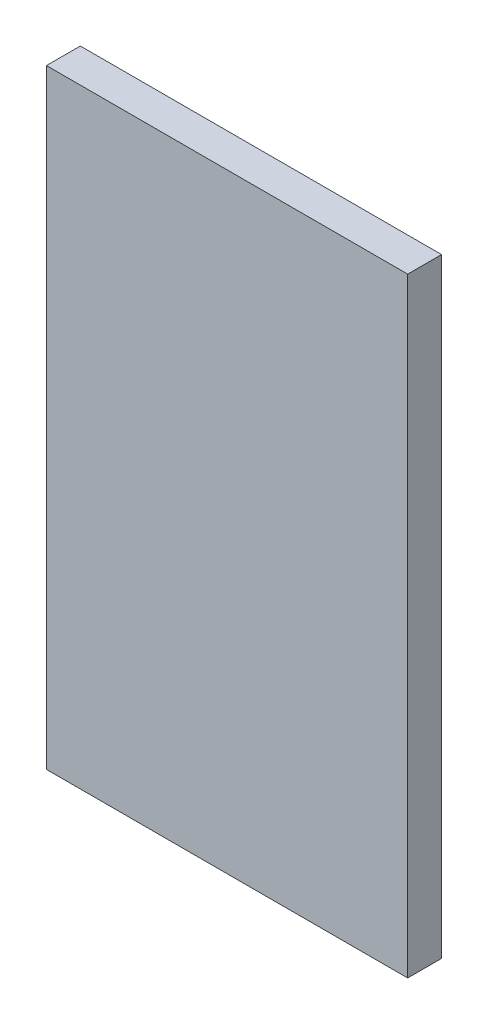
SolidWorks part; units mm, degrees
ref_plane "Front" through (0, 0, 0) normal (0, 0, 1) x (1, 0, 0)
ref_plane "Top" through (0, 0, 0) normal (0, 1, 0) x (1, 0, 0)
ref_plane "Right" through (0, 0, 0) normal (1, 0, 0) x (0, 0, -1)
sketch "Sketch1" plane through (0, 0, 0) normal (0, 0, 1) x (1, 0, 0)
  line L1 (-101.6, 171.45) -> (101.6, 171.45)
  line L2 (-101.6, 171.45) -> (-101.6, -171.45)
  line L3 (-101.6, -171.45) -> (101.6, -171.45)
  line L4 (101.6, 171.45) -> (101.6, -171.45)
  line L5 (-101.6, 171.45) -> (101.6, -171.45) construction
  line L6 (-101.6, -171.45) -> (101.6, 171.45) construction
  point P0 (0, 0)
  dimension "D1" = 203.2
  dimension "D2" = 342.9
extrude "Boss-Extrude1" add sketch "Sketch1" along normal blind 19.05
